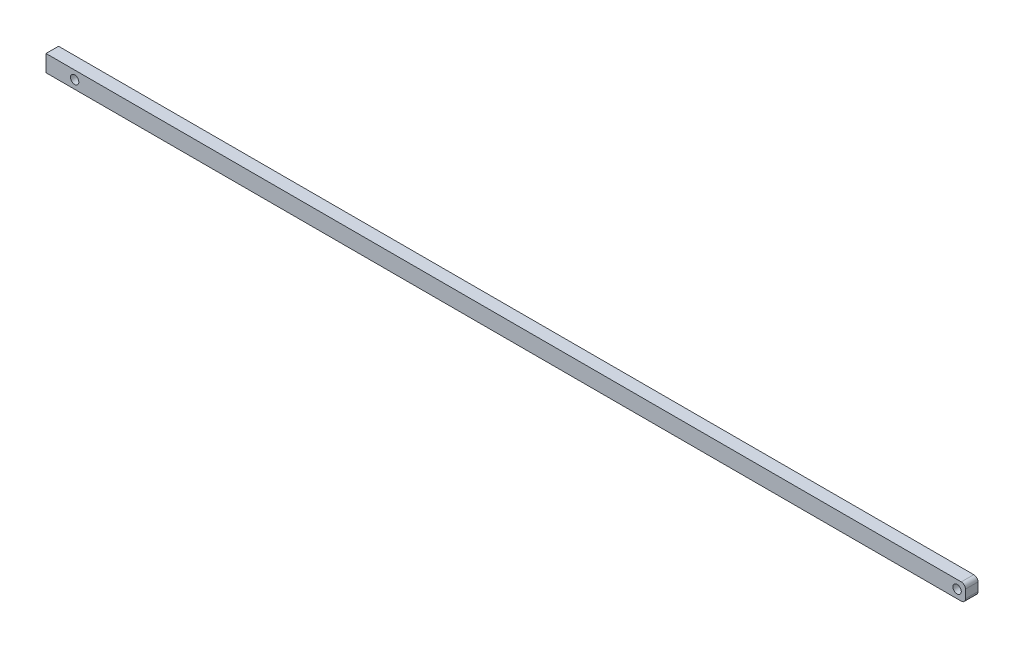
SolidWorks part; units mm, degrees
ref_plane "Plan de face" through (0, 0, 0) normal (0, 0, 1) x (1, 0, 0)
ref_plane "Plan de dessus" through (0, 0, 0) normal (0, 1, 0) x (1, 0, 0)
ref_plane "Plan de droite" through (0, 0, 0) normal (1, 0, 0) x (0, 0, -1)
sketch "Esquisse1" plane through (0, 0, 0) normal (0, 0, 1) x (1, 0, 0)
  line L1 (0, 0) -> (-220, 0)
  line L2 (0, 0) -> (0, 4)
  line L3 (0, 4) -> (-220, 4)
  line L4 (-220, 0) -> (-220, 4)
  dimension "D1" = 4
  dimension "D2" = 220
extrude "Boss.-Extru.1" add sketch "Esquisse1" along normal blind 3
sketch "Esquisse2" plane through (0, 0, 3) normal (0, 0, 1) x (1, 0, 0)
  line L0 (-220, 0) -> (0, 0) construction
  line L1 (0, 0) -> (0, 4) construction
  line L2 (-220, 0) -> (0, 0) construction
  circle A0 centre (-2, 2) radius 1
  circle A1 centre (-213.1504, 2) radius 1
  dimension "D1" = 2
  dimension "D3" = 2
  dimension "D4" = 2
  dimension "D2" = 2
extrude "Enlèv. mat.-Extru.1" cut sketch "Esquisse2" against normal blind 6
fillet "Congé1" radius 1 1 edges at (0, 4, 1.5)
fillet "Congé2" radius 1 1 edges at (0, 0, 1.5)
